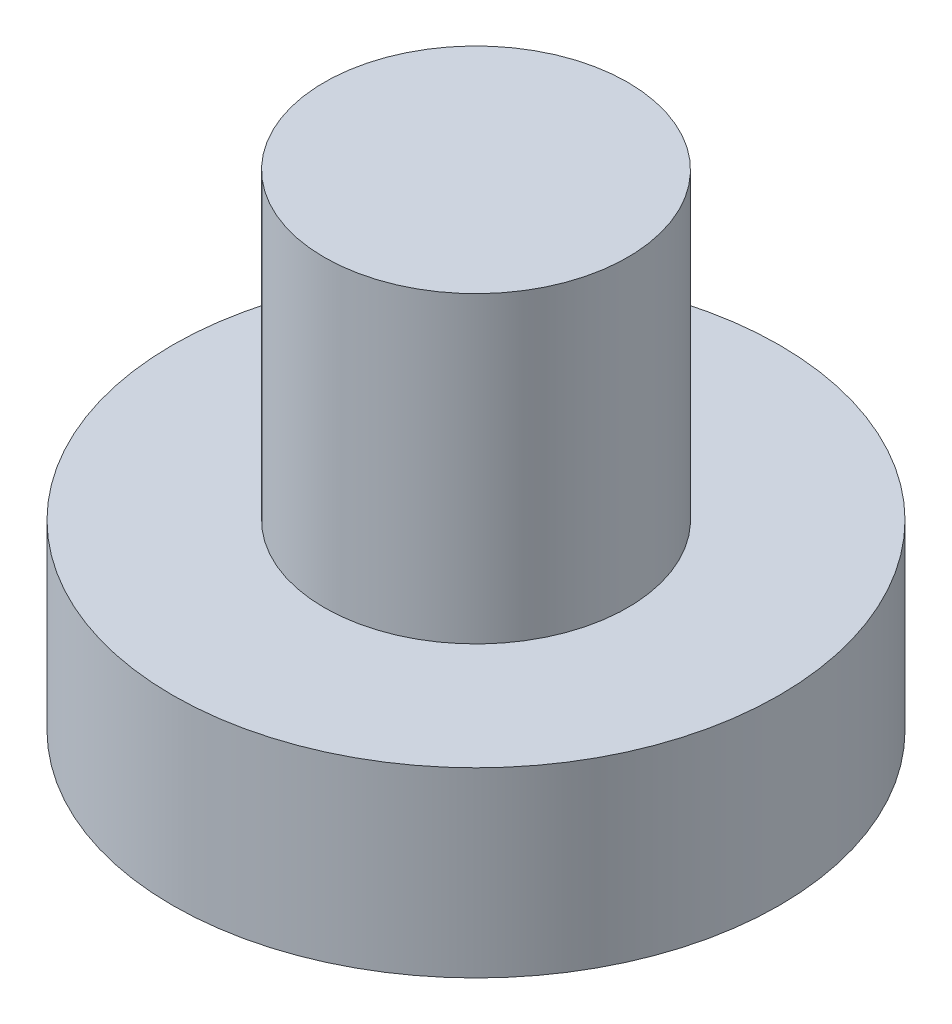
SolidWorks part; units mm, degrees
ref_plane "Plane1" through (0, 0, 0) normal (0, 0, 1) x (1, 0, 0)
ref_plane "Plane2" through (0, 0, 0) normal (0, 1, 0) x (1, 0, 0)
ref_plane "Plane3" through (0, 0, 0) normal (1, 0, 0) x (0, 0, -1)
sketch "Эскиз1" plane through (0, 0, 0) normal (0, 1, 0) x (1, 0, 0)
  circle A0 centre (0, 0) radius 50
  dimension "D1" = 100
extrude "Основание-Вытянуть" add sketch "Эскиз1" along normal blind 30
sketch "Эскиз2" plane through (0, 30, 0) normal (0, 1, 0) x (-1, 0, 0)
  circle A0 centre (0, 0) radius 25
  dimension "D1" = 50
extrude "Бобышка-Вытянуть1" add sketch "Эскиз2" along normal blind 50
